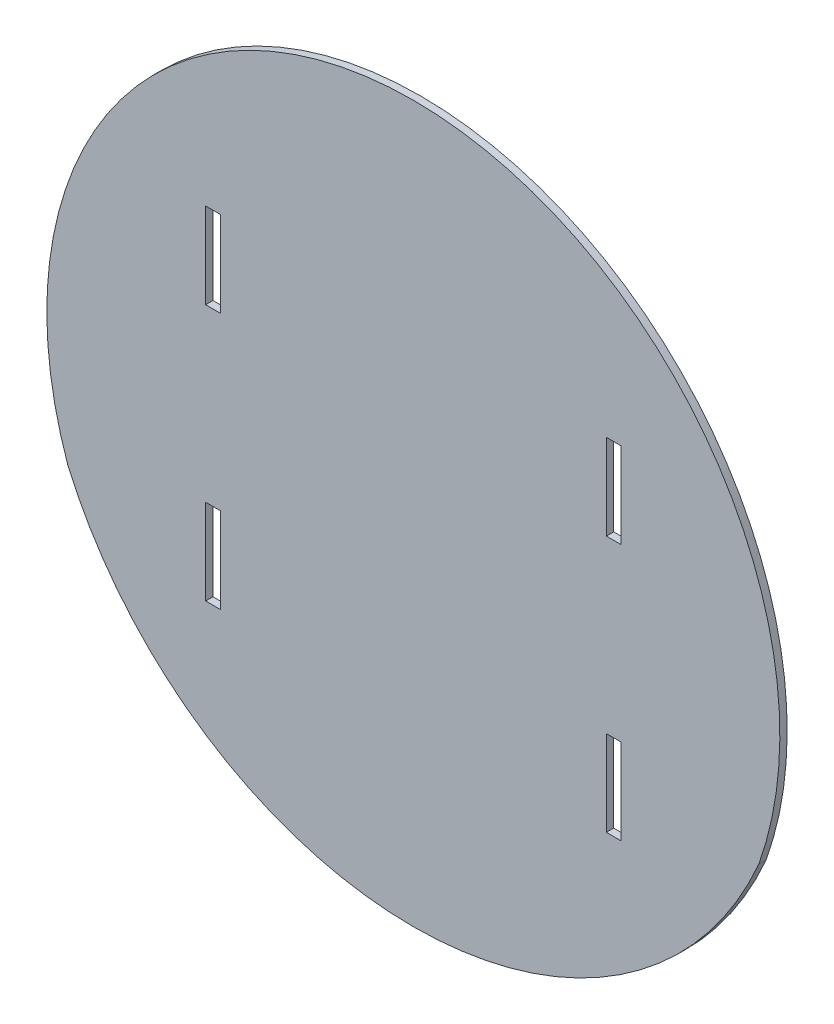
SolidWorks part; units mm, degrees
ref_plane "Plano frontal" through (0, 0, 0) normal (0, 0, 1) x (1, 0, 0)
ref_plane "Plano superior" through (0, 0, 0) normal (0, 1, 0) x (1, 0, 0)
ref_plane "Plano direito" through (0, 0, 0) normal (1, 0, 0) x (0, 0, -1)
sketch "Esboço1" plane through (0, 0, 0) normal (0, 0, 1) x (1, 0, 0)
  line L0 (0, 150) -> (0, -50) construction
  line L3 (-121.4214, 0) -> (-121.4214, 11) construction
  line L7 (0, 0) -> (-242.8427, 0) construction
  line L8 (-81.659, 70) -> (-20.2399, 70) construction
  line L9 (-79, -70) -> (-24.6269, -70) construction
  line L10 (-85, -70) -> (-85, -35)
  line L11 (-79, -70) -> (-79, -35)
  line L12 (-85, 70) -> (-79, 70)
  line L13 (-85, -70) -> (-79, -70)
  line L18 (-85, -35) -> (-79, -35)
  line L19 (-85, 35) -> (-79, 35)
  line L20 (-79, 35) -> (-79, 70)
  line L21 (-85, 35) -> (-85, 70)
  line L22 (85, -70) -> (79, -70)
  line L23 (85, -70) -> (85, -35)
  line L24 (85, -35) -> (79, -35)
  line L25 (79, -70) -> (79, -35)
  line L26 (85, 35) -> (85, 70)
  line L27 (85, 35) -> (79, 35)
  line L28 (79, 35) -> (79, 70)
  line L29 (85, 70) -> (79, 70)
  arc A0 (141.4214, -50) -> (-141.4214, -50) centre (0, 0) ccw
  arc A2 (141.4214, -50) -> (-141.4214, -50) centre (0, 11.0974) cw
  point P8 (-121.4214, -10)
  point P13 (-121.4214, 11)
  point P18 (-90, 70)
  point P21 (90, 70)
  point P22 (-150, 0)
  point P23 (-90, -70)
  point P24 (90, -70)
  point P27 (-85, 0)
  point P30 (-79, 0)
  dimension "D1" = 300
  dimension "D9" = 65
  dimension "D10" = 140
  dimension "D11" = 6
  dimension "D2" = 35
  dimension "D4" = 21
  dimension "D6" = 35
  dimension "D7" = 20
  dimension "D8" = 90
extrude "Ressalto-extrusão1" add sketch "Esboço1" along normal blind 3
